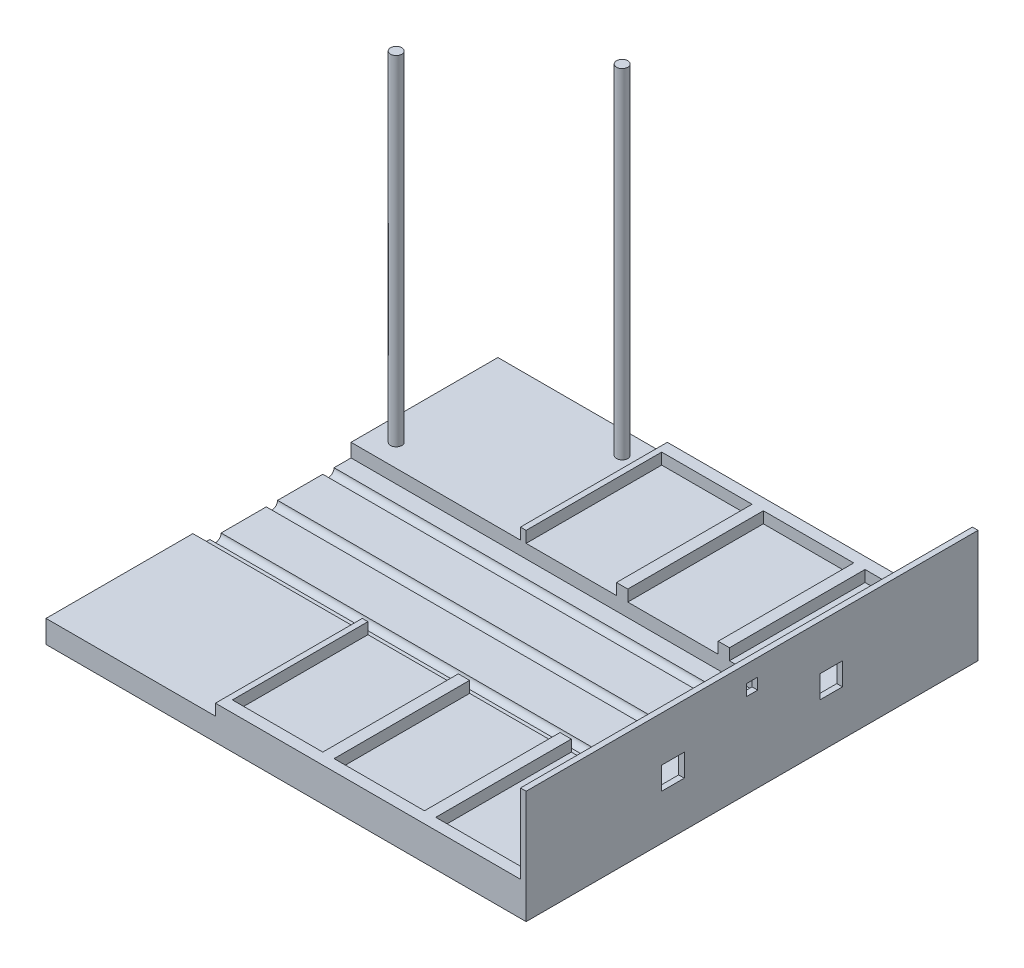
SolidWorks part; units mm, degrees
ref_plane "Front Plane" through (0, 0, 0) normal (0, 0, 1) x (1, 0, 0)
ref_plane "Top Plane" through (0, 0, 0) normal (0, 1, 0) x (1, 0, 0)
ref_plane "Right Plane" through (0, 0, 0) normal (1, 0, 0) x (0, 0, -1)
sketch "SingleLot" plane through (0, 0, 0) normal (0, 1, 0) x (1, 0, 0)
  line L0 (5, 70) -> (0, 70)
  line L1 (5, 70) -> (85, 70) construction
  line L2 (5, 70) -> (5, 190)
  line L3 (5, 190) -> (85, 190)
  line L4 (85, 70) -> (85, 190)
  line L5 (0, 70) -> (0, 200)
  line L6 (0, 200) -> (90, 200)
  line L7 (90, 200) -> (90, 70)
  line L8 (90, 70) -> (85, 70)
  dimension "D1" = 80
  dimension "D2" = 120
  dimension "D3" = 5
  dimension "D4" = 5
  dimension "D5" = 10
  dimension "D6" = 70
  dimension "D7" = 70
extrude "Parking" add sketch "SingleLot" along normal blind 10
pattern_linear "Parkings" count 3 spacing 90 along (1, 0, 0) of "Parking"
sketch "Wall" plane through (270, 0, 0) normal (1, 0, 0) x (0, 0, -1)
  line L0 (0, 65) -> (0, 80)
  line L2 (0, 0) -> (0, 55)
  line L3 (0, 80) -> (200, 80)
  line L4 (200, 0) -> (200, 80)
  line L5 (0, 65) -> (5, 65)
  line L7 (0, 55) -> (5, 55)
  line L8 (5, 65) -> (5, 55)
  line L11 (200, 0) -> (200, -20)
  line L12 (200, -20) -> (0, -20)
  line L13 (0, 0) -> (0, -20)
  dimension "D1" = 80
  dimension "D2" = 5
  dimension "D3" = 10
  dimension "D4" = 15
  dimension "D5" = 20
extrude "RightWall" add sketch "Wall" along normal blind 5
sketch "Sketch2" plane through (275, 0, 0) normal (1, 0, 0) x (0, 0, -1)
  line L1 (80, 40) -> (60, 40)
  line L2 (80, 40) -> (80, 20)
  line L3 (80, 20) -> (60, 20)
  line L4 (60, 40) -> (60, 20)
  line L7 (70, 10) -> (70, 0) construction
  line L8 (70, 10) -> (200, 10) construction
  dimension "D1" = 20
  dimension "D2" = 20
  dimension "D3" = 10
  dimension "D4" = 10
extrude "LaserHole" cut sketch "Sketch2" against normal up to next
sketch "Sketch5" plane through (0, 0, 0) normal (0, -1, 0) x (1, 0, 0)
  line L0 (0, -200) -> (0, -70) construction
  line L1 (270, -70) -> (-150, -70)
  line L2 (270, -70) -> (270, -200)
  line L3 (270, -200) -> (-150, -200)
  line L4 (-150, -70) -> (-150, -200)
  dimension "D1" = 150
extrude "ParkingBottom" add sketch "Sketch5" along normal blind 20
sketch "Sketch8" plane through (-150, 0, 0) normal (-1, 0, 0) x (0, 0, 1)
  line L0 (-70, 0) -> (-200, 0) construction
  line L1 (-70, -20) -> (0, -20)
  line L2 (-70, -20) -> (-70, -12)
  line L3 (-70, -12) -> (-55, -12)
  line L4 (0, -20) -> (0, -17)
  line L5 (-70, -20) -> (-70, 0) construction
  line L6 (0, 0) -> (0, -20) construction
  line L7 (-45, -12) -> (-5, -12)
  arc A0 (-55, -12) -> (-45, -12) centre (-50, -12) ccw
  arc A1 (-5, -12) -> (0, -17) centre (0, -12) ccw
  dimension "D1" = 10
  dimension "D2" = 10
  dimension "D3" = 12
  dimension "D4" = 20
  dimension "D5" = 3
  dimension "D6" = 65
extrude "CartBottom" add sketch "Sketch8" against normal up to vertex (425 mm away)
mirror "Mirror8" about plane through (0, 0, 0) normal (0, 0, 1) of bodies 115
sketch "Sketch9" plane through (0, 0, 0) normal (0, 1, 0) x (1, 0, 0)
  line L0 (-150, 70) -> (-150, 200) construction
  line L1 (0, 70) -> (-150, 70) construction
  line L2 (0, 200) -> (0, 70) construction
  line L3 (-150, 200) -> (0, 200) construction
  circle A0 centre (-130, 90) radius 5
  circle A1 centre (-20, 180) radius 5
  dimension "D3" = 10
  dimension "D6" = 10
  dimension "D1" = 20
  dimension "D2" = 20
  dimension "D4" = 20
  dimension "D5" = 20
extrude "ThreadedRod" add sketch "Sketch9" along normal blind 300
